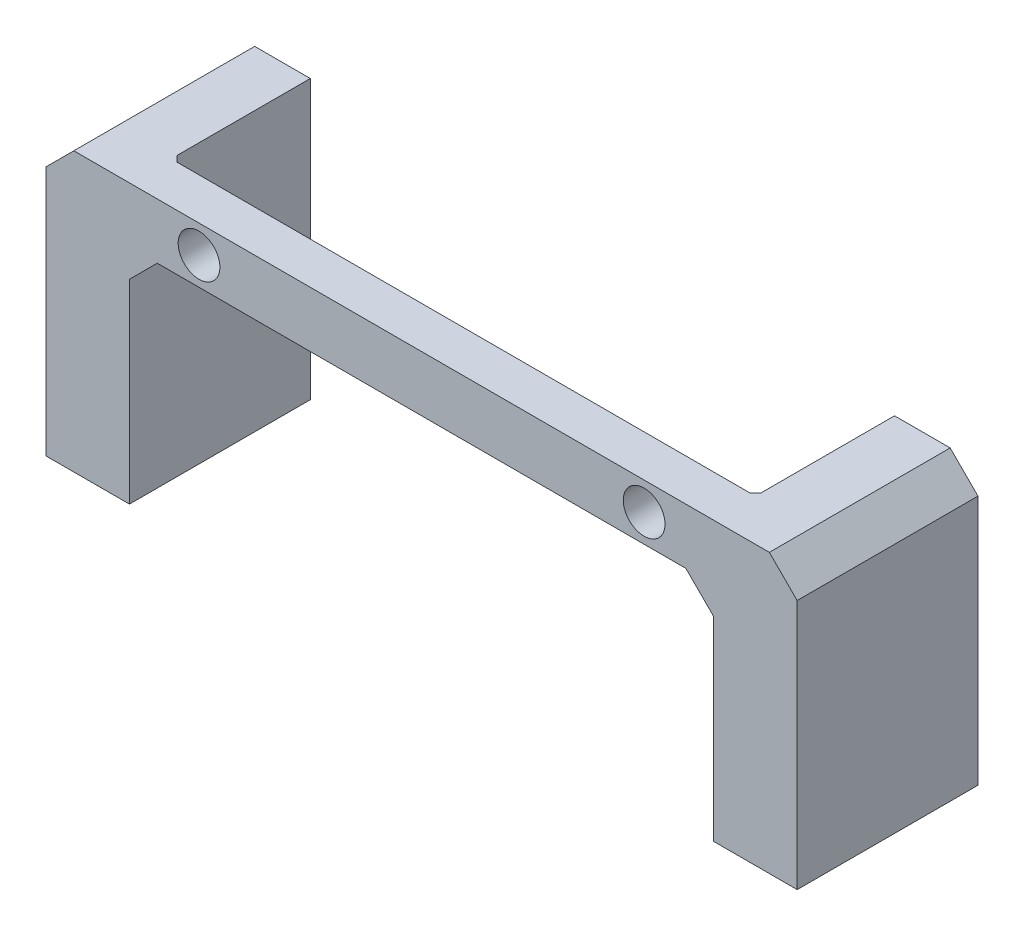
SolidWorks part; units mm, degrees
ref_plane "前基準面" through (0, 0, 0) normal (0, 0, 1) x (1, 0, 0)
ref_plane "上基準面" through (0, 0, 0) normal (0, 1, 0) x (1, 0, 0)
ref_plane "右基準面" through (0, 0, 0) normal (1, 0, 0) x (0, 0, -1)
sketch "草圖1" plane through (0, 0, 0) normal (0, 0, 1) x (1, 0, 0)
  line L1 (-27, 10) -> (27, 10)
  line L2 (-27, 10) -> (-27, -10)
  line L3 (-27, -10) -> (27, -10)
  line L4 (27, 10) -> (27, -10)
  point P4 (0, 10)
  point P6 (-27, 0)
  dimension "D1" = 54
  dimension "D2" = 20
extrude "填料-伸長1" add sketch "草圖1" along normal blind 13
sketch "草圖2" plane through (0, 0, 13) normal (0, 0, 1) x (1, 0, 0)
  line L0 (-27, -10) -> (27, -10) construction
  line L1 (-21, 6) -> (21, 6)
  line L2 (-21, 6) -> (-21, -10)
  line L3 (-21, -10) -> (21, -10)
  line L4 (21, 6) -> (21, -10)
  line L5 (27, 10) -> (-27, 10) construction
  point P6 (0, 6)
  dimension "D1" = 42
  dimension "D2" = 4
extrude "除料-伸長1" cut sketch "草圖2" against normal through all
sketch "草圖3" plane through (0, 0, 13) normal (0, 0, 1) x (1, 0, 0)
  line L0 (27, 10) -> (-27, 10) construction
  circle A0 centre (-16, 8) radius 1.5
  circle A1 centre (16, 8) radius 1.5
  dimension "D3" = 3
  dimension "D4" = 3
  dimension "D1" = 32
  dimension "D2" = 16
  dimension "D5" = 2
extrude "除料-伸長2" cut sketch "草圖3" against normal through all
sketch "草圖4" plane through (0, -10, 0) normal (0, -1, 0) x (1, 0, 0)
  line L0 (0, 0) -> (0, 13) construction
  line L1 (21, 0) -> (-21, 0) construction
  line L2 (21, 13) -> (-21, 13) construction
  line L3 (-27, 13) -> (-21, 13) construction
  circle A0 centre (-24, 5) radius 1.5
  circle A1 centre (24, 5) radius 1.5
  dimension "D1" = 3
  dimension "D2" = 8
extrude "除料-伸長3" cut sketch "草圖4" against normal blind 13
sketch "草圖5" plane through (0, 10, 0) normal (0, 1, 0) x (1, 0, 0)
  line L0 (27, 0) -> (-27, 0) construction
  line L1 (-21, 0) -> (21, 0)
  line L2 (-21, 0) -> (-21, -10)
  line L3 (-21, -10) -> (21, -10)
  line L4 (21, 0) -> (21, -10)
  point P6 (0, -10)
  dimension "D1" = 42
  dimension "D2" = 10
extrude "除料-伸長4" cut sketch "草圖5" against normal through all
chamfer "導角1" distance 2 angle 45 2 edges at (-27, 10, 6.5) (27, 10, 6.5)
chamfer "導角2" distance 2 angle 45 2 edges at (21, 6, 11.5) (-21, 6, 11.5)
chamfer "導角3" distance 0.4 angle 45 2 edges at (21, 7, 10) (-21, 7, 10)
